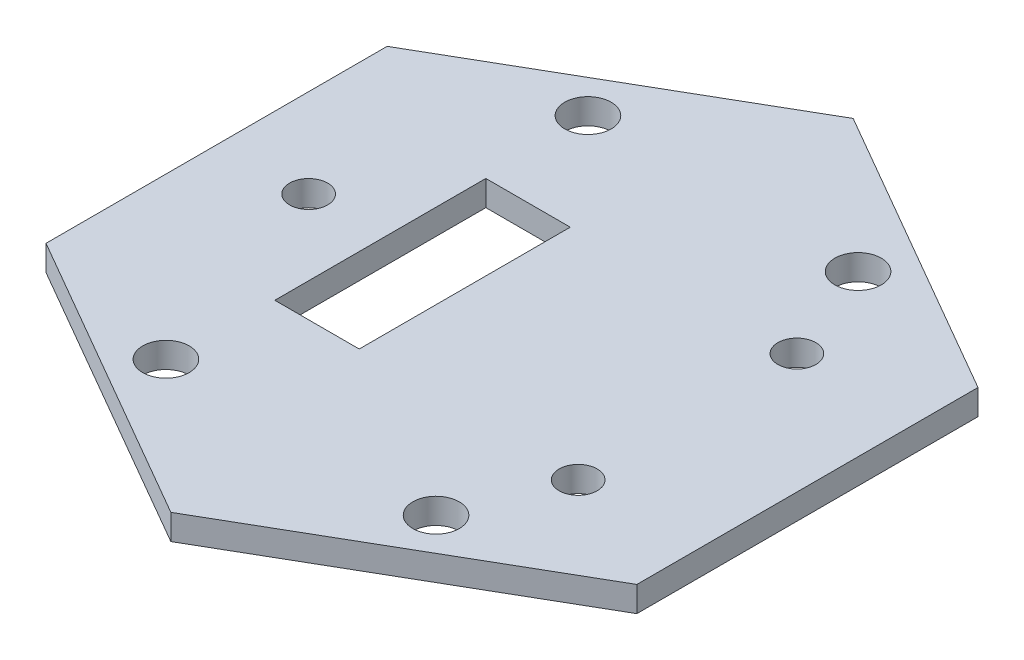
SolidWorks part; units mm, degrees
ref_plane "Plan de face" through (0, 0, 0) normal (0, 0, 1) x (1, 0, 0)
ref_plane "Plan de dessus" through (0, 0, 0) normal (0, 1, 0) x (1, 0, 0)
ref_plane "Plan de droite" through (0, 0, 0) normal (1, 0, 0) x (0, 0, -1)
sketch "Sketch1" plane through (0, 0, 0) normal (0, 1, 0) x (1, 0, 0)
  line L0 (-16, 25) -> (16, 25) construction
  line L1 (-16, -25) -> (16, -25) construction
  line L4 (0, -40.4145) -> (35, -20.2073)
  line L9 (35, -20.2073) -> (35, 20.2073)
  line L10 (35, 20.2073) -> (0, 40.4145)
  line L11 (-15.5994, 12.5) -> (-5.5994, 12.5)
  line L14 (0, 40.4145) -> (-35, 20.2073)
  line L15 (-35, 20.2073) -> (-35, -20.2073)
  line L16 (-35, -20.2073) -> (0, -40.4145)
  line L17 (-15.5994, 12.5) -> (-15.5994, -12.5)
  line L18 (-15.5994, -12.5) -> (-5.5994, -12.5)
  line L19 (-5.5994, 12.5) -> (-5.5994, -12.5)
  circle A5 centre (0, 25) radius 4
  circle A6 centre (0, -25) radius 4
  circle A8 centre (0, 0) radius 35 construction
  circle A11 centre (20.7927, 12.9582) radius 2.25
  circle A12 centre (20.7944, -12.9554) radius 2.25
  circle A13 centre (-24.5, 0.4062) radius 2.25
  circle A14 centre (-16, 25) radius 2.75
  circle A15 centre (16, 25) radius 2.75
  circle A16 centre (-16, -25) radius 2.75
  circle A17 centre (16, -25) radius 2.75
  point P4 (0, 0)
  point P26 (0, 25)
  point P28 (20.772, -12.9913)
  point P30 (0, -25)
  point P31 (-15.5994, 0)
  point P33 (20.772, 12.9582)
  point P37 (20.7927, -12.9554)
  dimension "D1" = 70
  dimension "D2" = 5.5
  dimension "D3" = 25
  dimension "D4" = 25
  dimension "D7" = 24.5
  dimension "D8" = 8
  dimension "D5" = 10
  dimension "D6" = 25
  dimension "D10" = 4.5
  dimension "D11" = 4.5
  dimension "D12" = 4.5
  dimension "D14" = 8
  dimension "D15" = 5.5
  dimension "D16" = 5.5
  dimension "D17" = 5.5
  dimension "D9" = 24.5
  dimension "D13" = 24.5
  dimension "D18" = 32
  dimension "D19" = 32
extrude "Boss-Extrude1" add sketch "Sketch1" along normal blind 3
